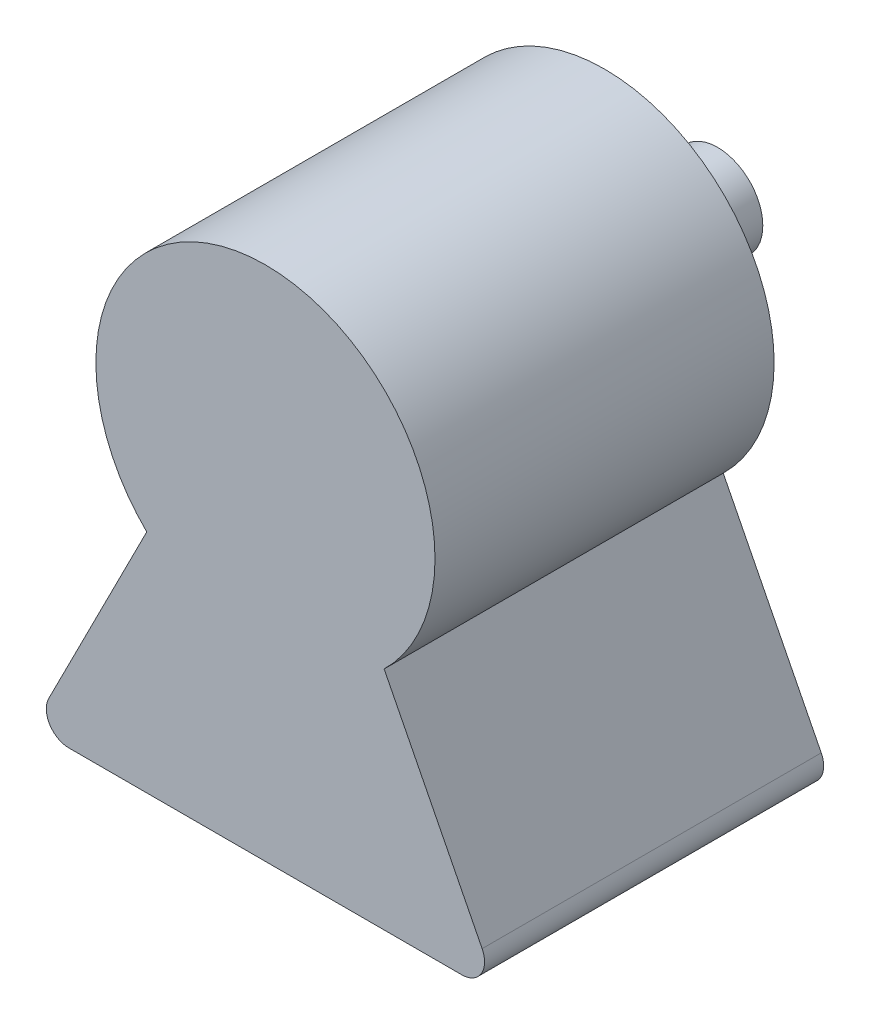
SolidWorks part; units mm, degrees
material "6061 Alloy"
ref_plane "Front Plane" through (0, 0, 0) normal (0, 0, 1) x (1, 0, 0)
ref_plane "Top Plane" through (0, 0, 0) normal (0, 1, 0) x (1, 0, 0)
ref_plane "Right Plane" through (0, 0, 0) normal (1, 0, 0) x (0, 0, -1)
sketch "Sketch1" plane through (0, 0, 0) normal (0, 0, 1) x (1, 0, 0)
  circle A0 centre (0, 0) radius 2
  dimension "D1" = 4
extrude "Boss-Extrude1" add sketch "Sketch1" along normal blind 5
sketch "Sketch2" plane through (0, 0, 5) normal (0, 0, 1) x (1, 0, 0)
  circle A0 centre (0, 0) radius 7.5
  dimension "D1" = 15
extrude "Boss-Extrude2" add sketch "Sketch2" along normal blind 15
sketch "Sketch3" plane through (0, 0, 20) normal (0, 0, 1) x (1, 0, 0)
  line L0 (-5.2497, -5.3564) -> (-10.3217, -15.3551)
  line L1 (-10.3217, -15.3551) -> (10.3217, -15.3551)
  line L2 (10.3217, -15.3551) -> (5.2497, -5.3564)
  line L3 (-5.2497, -5.3564) -> (5.2497, -5.3564)
  circle A0 centre (0, 0) radius 7.5 construction
  point P7 (0, -15.3551)
extrude "Boss-Extrude3" add sketch "Sketch3" against normal blind 15
fillet "Fillet1" radius 1 2 edges at (10.3217, -15.3551, 12.5) (-10.3217, -15.3551, 12.5)
